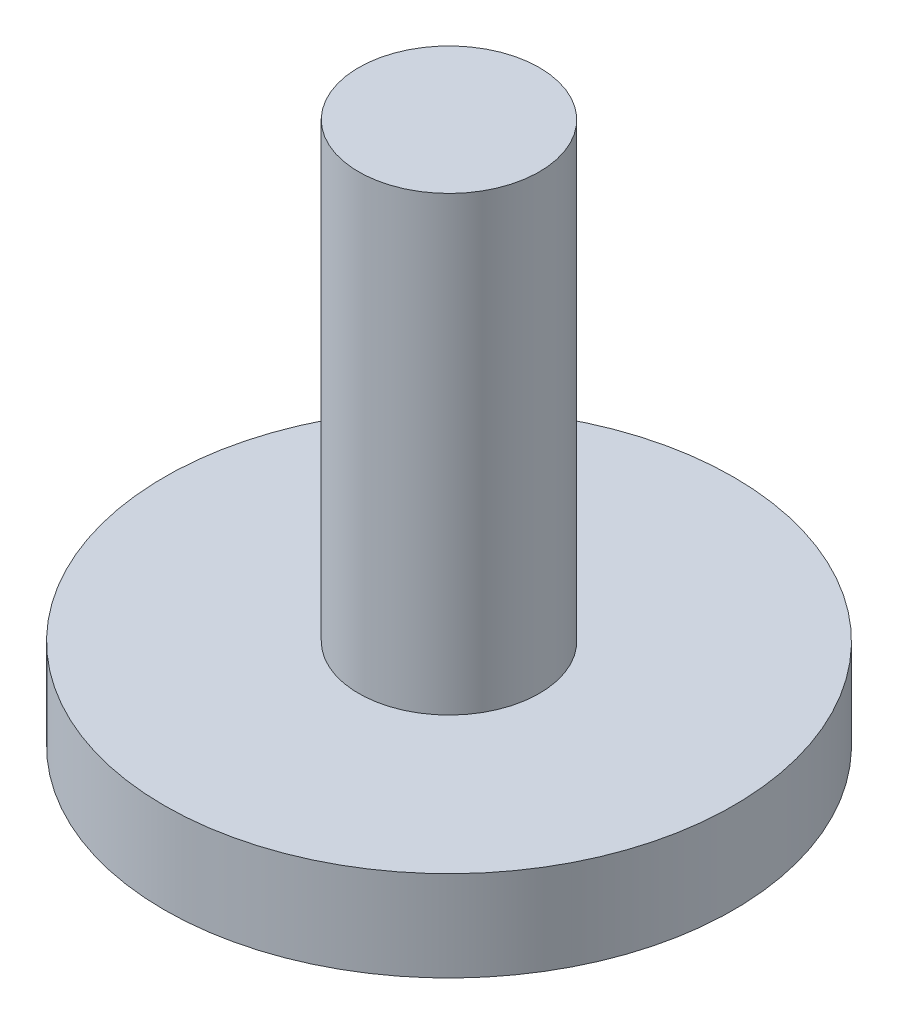
SolidWorks part; units mm, degrees
ref_plane "Front" through (0, 0, 0) normal (0, 0, 1) x (1, 0, 0)
ref_plane "Top" through (0, 0, 0) normal (0, 1, 0) x (1, 0, 0)
ref_plane "Side" through (0, 0, 0) normal (1, 0, 0) x (0, 0, -1)
sketch "Sketch1" plane through (0, 0, 0) normal (0, 0, 1) x (1, 0, 0)
  line L0 (0, 0) -> (0, 22.3396) construction
  line L1 (0, 0) -> (-15.75, 0)
  line L2 (-15.75, 0) -> (-15.75, 5)
  line L3 (-15.75, 5) -> (-5, 5)
  line L4 (-5, 5) -> (-5, 30)
  line L5 (-5, 30) -> (0, 30)
  line L6 (0, 30) -> (0, 0)
  dimension "D1" = 31.5
  dimension "D2" = 10
  dimension "D3" = 5
  dimension "D4" = 25
revolve "Revolve1" add sketch "Sketch1" angle 360 about L0
